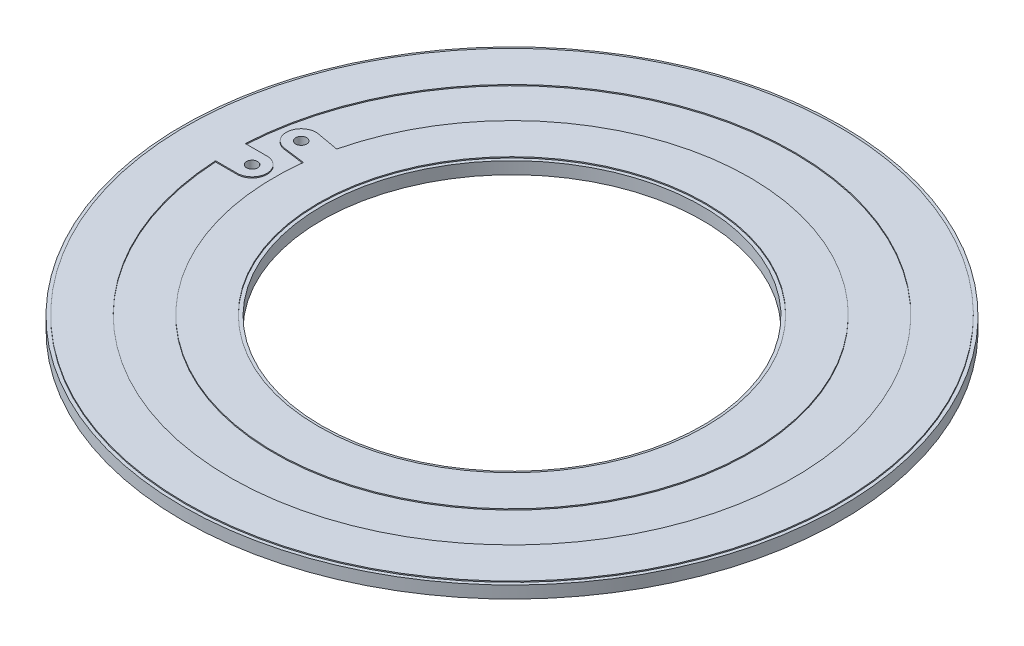
SolidWorks part; units mm, degrees
ref_plane "Спереди" through (0, 0, 0) normal (0, 0, 1) x (1, 0, 0)
ref_plane "Сверху" through (0, 0, 0) normal (0, 1, 0) x (1, 0, 0)
ref_plane "Справа" through (0, 0, 0) normal (1, 0, 0) x (0, 0, -1)
sketch "Эскиз1" plane through (0, 0, 0) normal (0, 1, 0) x (1, 0, 0)
  circle A0 centre (0, 0) radius 17.2
  circle A1 centre (0, 0) radius 29.8
  dimension "D1" = 34.4
  dimension "D2" = 59.6
extrude "Бобышка-Вытянуть1" add sketch "Эскиз1" along normal blind 1.1
sketch "Эскиз2" plane through (0, 1.1, 0) normal (0, 1, 0) x (1, 0, 0)
  circle A0 centre (0, 0) radius 29.5
  circle A1 centre (0, 0) radius 25.5
  circle A2 centre (0, 0) radius 21.5
  circle A3 centre (0, 0) radius 17.5
  circle A5 centre (0, 0) radius 17.2 construction
  circle A7 centre (0, 0) radius 29.8 construction
  dimension "D1" = 4
  dimension "D2" = 4
  dimension "D3" = 4
  dimension "D4" = 0.3
extrude "Бобышка-Вытянуть2" add sketch "Эскиз2" along normal blind 0.1 contours A2 A3 | A0 A1
sketch "Эскиз4" plane through (0, 1.1, 0) normal (0, 1, 0) x (1, 0, 0)
  line L0 (0, 0) -> (-33.7363, 0) construction
  circle A0 centre (-23.5, 0) radius 0.5
  circle A3 centre (0, 0) radius 23.5 construction
  circle A4 centre (0, 0) radius 21.5 construction
  dimension "D1" = 2
  dimension "D2" = 1
extrude "Вырез-Вытянуть1" cut sketch "Эскиз4" against normal through all
sketch "Эскиз5" plane through (0, 1.1, 0) normal (0, 1, 0) x (1, 0, 0)
  circle A1 centre (-23.5, 0) radius 0.5 construction
  circle A3 centre (-23.5, 0) radius 1.3459
  circle A4 centre (-23.5, 0) radius 0.5
extrude "Бобышка-Вытянуть3" add sketch "Эскиз5" along normal blind 0.1
ref_axis "Ось1" through (0, 1.1, 0) along (0, -1, 0)
pattern_circular "Круговой массив1" count 2 over 10 about axis through (0, 1.1, 0) along (0, -1, 0) of "Вырез-Вытянуть1", "Бобышка-Вытянуть3"
sketch "Эскиз6" plane through (0, 1.1, 0) normal (0, 1, 0) x (1, 0, 0)
  line L2 (-23.143, 4.0807) -> (0, 0) construction
  line L3 (-22.8005, 5.3824) -> (-20.8992, 5.0471)
  line L4 (-23.2664, 2.7405) -> (-21.3553, 2.4903)
  line L5 (-23.5, -1.3459) -> (-27.4565, -1.3459)
  line L6 (-23.5, 1.3459) -> (-27.4565, 1.3459)
  line L7 (-27.4565, 1.3459) -> (-27.4565, -1.3459)
  line L8 (-23.5, -1.3459) -> (-24.4128, 0)
  line L9 (-24.4128, 0) -> (-23.5, 1.3459)
  circle A5 centre (-23.143, 4.0807) radius 1.3459 construction
  circle A6 centre (-23.143, 4.0807) radius 1.3459 construction
  circle A7 centre (0, 0) radius 21.5
  arc A8 (-20.8992, 5.0471) -> (-21.3553, 2.4903) centre (0, 0) ccw
  arc A9 (-23.2664, 2.7405) -> (-22.8005, 5.3824) centre (-23.143, 4.0807) ccw
  circle A19 centre (-23.5, 0) radius 1.3459 construction
  circle A20 centre (-23.5, 0) radius 1.3459 construction
  dimension "D1" = 0
extrude "Бобышка-Вытянуть4" add sketch "Эскиз6" along normal blind 0.1
